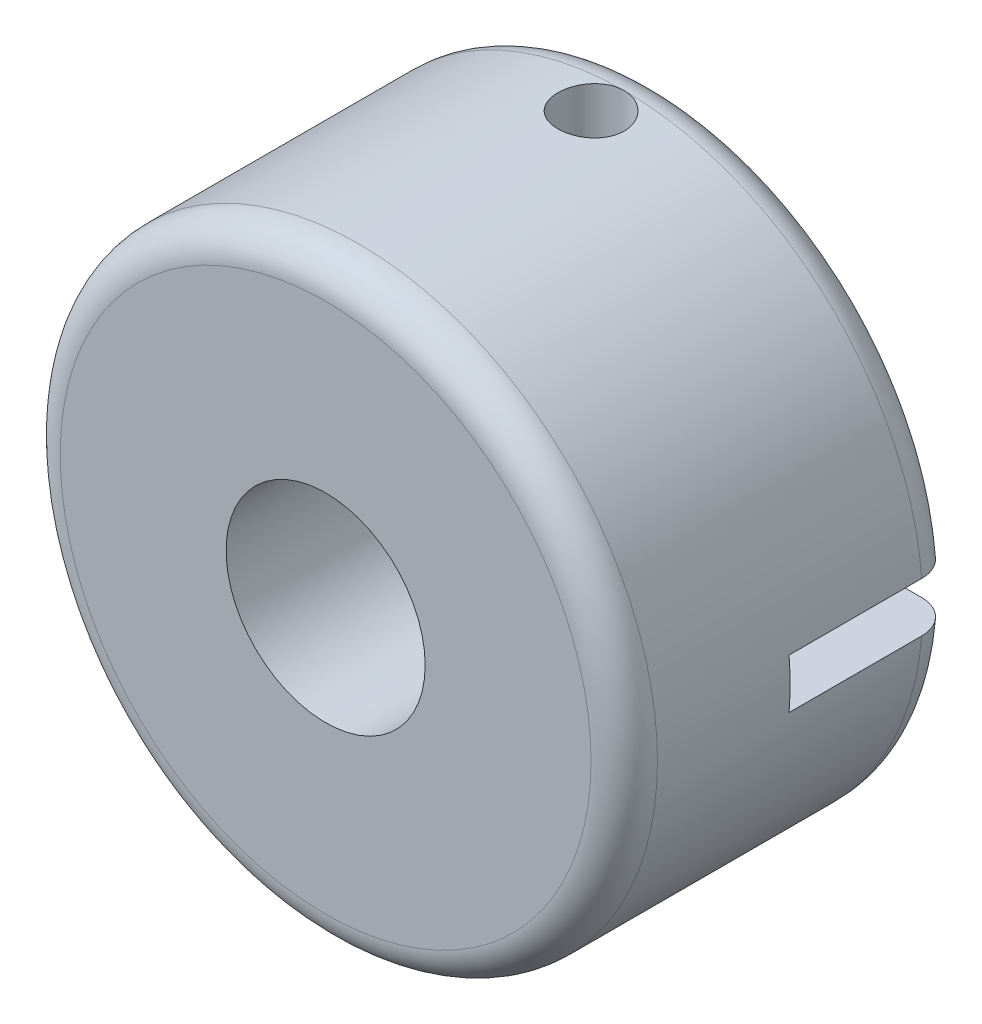
SolidWorks part; units mm, degrees
material "黄铜"
ref_plane "前视基准面" through (0, 0, 0) normal (0, 0, 1) x (1, 0, 0)
ref_plane "上视基准面" through (0, 0, 0) normal (0, 1, 0) x (1, 0, 0)
ref_plane "右视基准面" through (0, 0, 0) normal (1, 0, 0) x (0, 0, -1)
sketch "草图1" plane through (0, 0, 0) normal (0, 0, 1) x (1, 0, 0)
  circle A0 centre (0, 0) radius 9
  dimension "D1" = 18
extrude "凸台-拉伸1" add sketch "草图1" along normal blind 10
sketch "草图2" plane through (0, 0, 0) normal (1, 0, 0) x (0, 0, -1)
  line L0 (0, -9) -> (0, 9) construction
  line L1 (5, 0.75) -> (-5, 0.75)
  line L2 (5, 0.75) -> (5, -0.75)
  line L3 (5, -0.75) -> (-5, -0.75)
  line L4 (-5, 0.75) -> (-5, -0.75)
  line L5 (5, 0.75) -> (-5, -0.75) construction
  line L6 (5, -0.75) -> (-5, 0.75) construction
  point P0 (0, 0)
  dimension "D1" = 1.5
  dimension "D2" = 5
extrude "切除-拉伸1" cut sketch "草图2" against normal through all both and the other way through all
sketch "草图3" plane through (0, 0, 0) normal (0, 1, 0) x (1, 0, 0)
  circle A0 centre (0, -2) radius 1
  dimension "D1" = 2
  dimension "D2" = 2
extrude "切除-拉伸2" cut sketch "草图3" against normal through all both and the other way through all
fillet "圆角1" radius 1 3 edges at (9, 0, 10) (0, 9, 0) (0, -9, 0)
sketch "草图4" plane through (0, 0, 10) normal (0, 0, 1) x (1, 0, 0)
  circle A0 centre (0, 0) radius 3
  dimension "D1" = 6
extrude "切除-拉伸3" cut sketch "草图4" against normal blind 6
